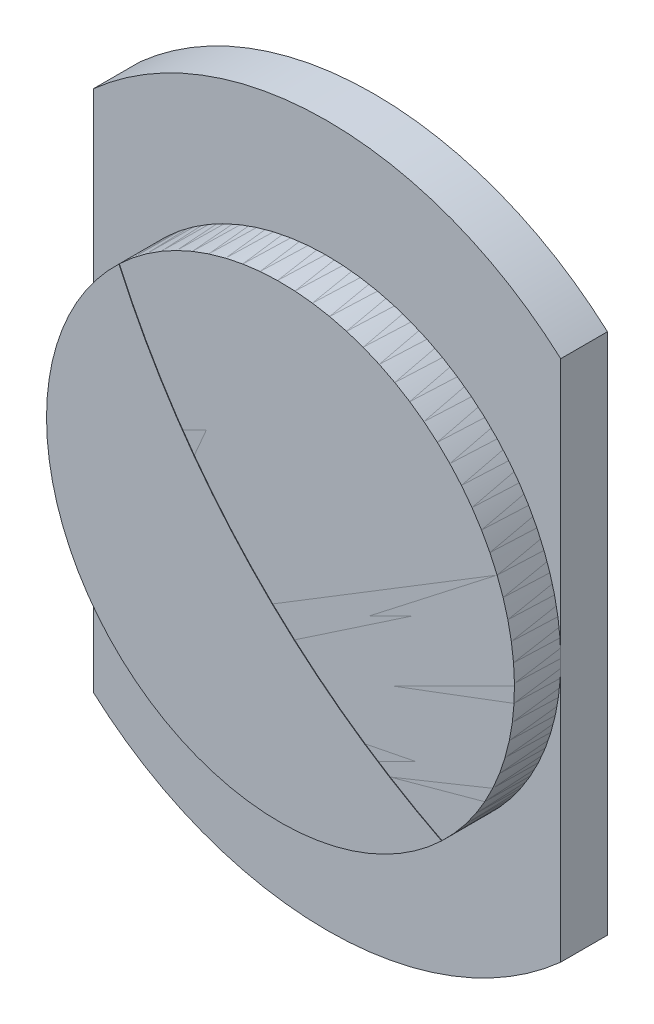
SolidWorks part; units mm, degrees
ref_plane "Front Plane" through (0, 0, 0) normal (1, 0, 0) x (0, 1, 0)
ref_plane "Top Plane" through (0, 0, 0) normal (0, 0, 1) x (0, 1, 0)
ref_plane "Right Plane" through (0, 0, 0) normal (0, 1, 0) x (-1, 0, 0)
sketch "Sketch1" plane through (0, 0, 0) normal (0, 0, 1) x (0, 1, 0)
  circle A0 centre (0, 0) radius 7.5
  dimension "D1" = 15
extrude "Boss-Extrude1" add sketch "Sketch1" along normal blind 1
sketch "Sketch2" plane through (0, 0, 1) normal (0, 0, 1) x (1, 0, 0)
  circle A0 centre (0, 0) radius 5
  dimension "D1" = 10
extrude "Boss-Extrude2" add sketch "Sketch2" along normal blind 1
sketch "Sketch3" plane through (0, 0, 1) normal (0, 0, 1) x (1, 0, 0)
  line L0 (5, 5.5902) -> (5, -5.5902)
  line L5 (-5, 5.5902) -> (-5, -5.5902)
  circle A0 centre (0, 0) radius 7.5 construction
  circle A1 centre (0, 0) radius 5 construction
  circle A2 centre (0, 0) radius 5
  point P0 (0, 0)
extrude "Cut-Extrude2" cut sketch "Sketch3" against normal up to next
sketch "Sketch4" plane through (0, 0, 2) normal (0, 0, 1) x (0, -1, 0)
  line L0 (-3.6182, -3.4509) -> (3.6182, 3.4509) construction
  circle A0 centre (-9.7607, 10.2337) radius 15
  circle A1 centre (0, 0) radius 5 construction
  dimension "D1" = 30
extrude "Cut-Extrude3" cut sketch "Sketch4" against normal blind 0.01
sketch "Sketch5" plane through (0, 0, 1.99) normal (0, 0, 1) x (1, 0, 0)
  arc A2 (3.4509, -3.6182) -> (-3.4509, 3.6182) centre (0, 0) ccw
  arc A3 (-3.4509, 3.6182) -> (3.4509, -3.6182) centre (10.2337, 9.7607) ccw
  arc A4 (3.4509, -3.6182) -> (-3.4509, 3.6182) centre (0, 0) ccw
  arc A5 (-3.4509, 3.6182) -> (3.4509, -3.6182) centre (10.2337, 9.7607) ccw
  dimension "D1" = 0
extrude "Boss-Extrude3" add sketch "Sketch5" against normal up to surface (1.99 mm away) separate body up to face at (0, 0, 0)
